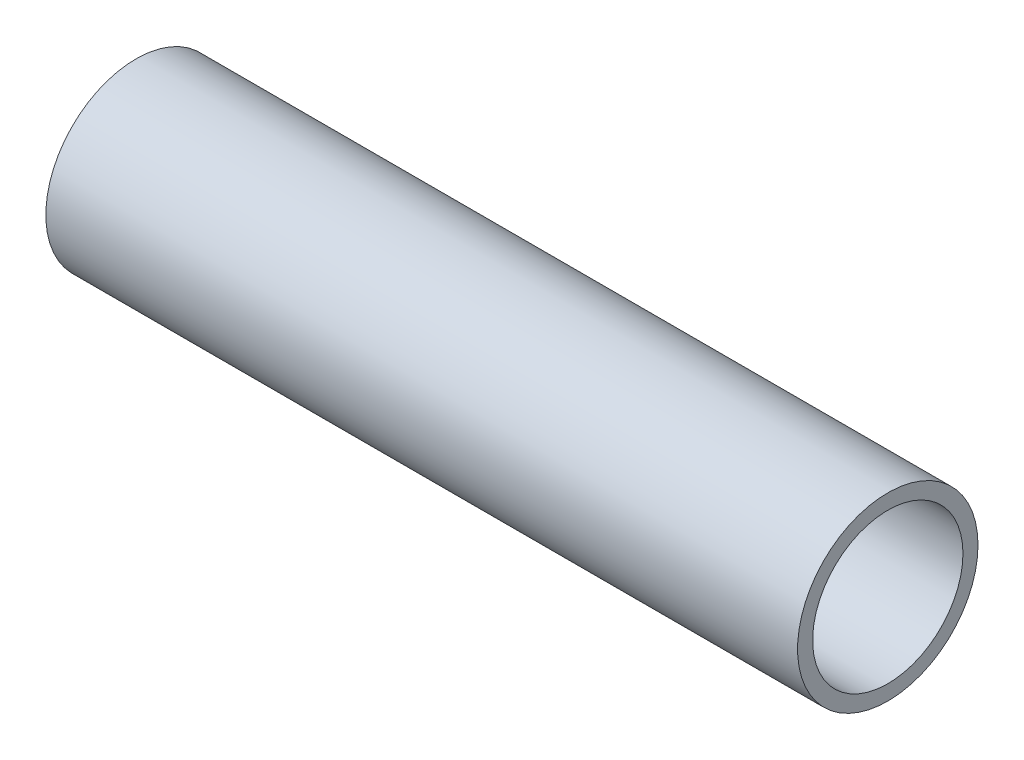
SolidWorks part; units mm, degrees
ref_plane "Front Plane" through (0, 0, 0) normal (0, 0, 1) x (1, 0, 0)
ref_plane "Top Plane" through (0, 0, 0) normal (0, 1, 0) x (1, 0, 0)
ref_plane "Right Plane" through (0, 0, 0) normal (1, 0, 0) x (0, 0, -1)
sketch "Sketch1" plane through (0, 0, 0) normal (1, 0, 0) x (0, 0, -1)
  circle A0 centre (0, 0) radius 6
  circle A1 centre (0, 0) radius 5
extrude "Boss-Extrude1" add sketch "Sketch1" along normal blind 50
